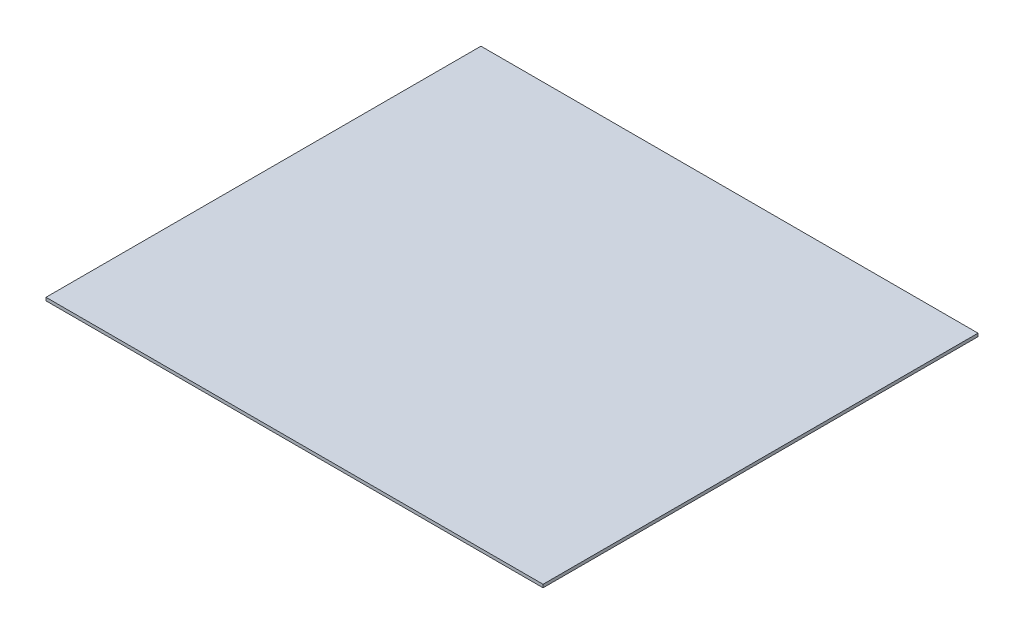
SolidWorks part; units mm, degrees
ref_plane "前视基准面" through (0, 0, 0) normal (0, 0, 1) x (1, 0, 0)
ref_plane "上视基准面" through (0, 0, 0) normal (0, 1, 0) x (1, 0, 0)
ref_plane "右视基准面" through (0, 0, 0) normal (1, 0, 0) x (0, 0, -1)
sketch "草图1" plane through (0, 0, 0) normal (0, 1, 0) x (1, 0, 0)
  line L0 (0, 0) -> (-800, 0)
  line L1 (-800, 0) -> (-800, 700)
  line L2 (-800, 700) -> (0, 700)
  line L3 (0, 700) -> (0, 0)
extrude "凸台-拉伸1" add sketch "草图1" along normal blind 5
